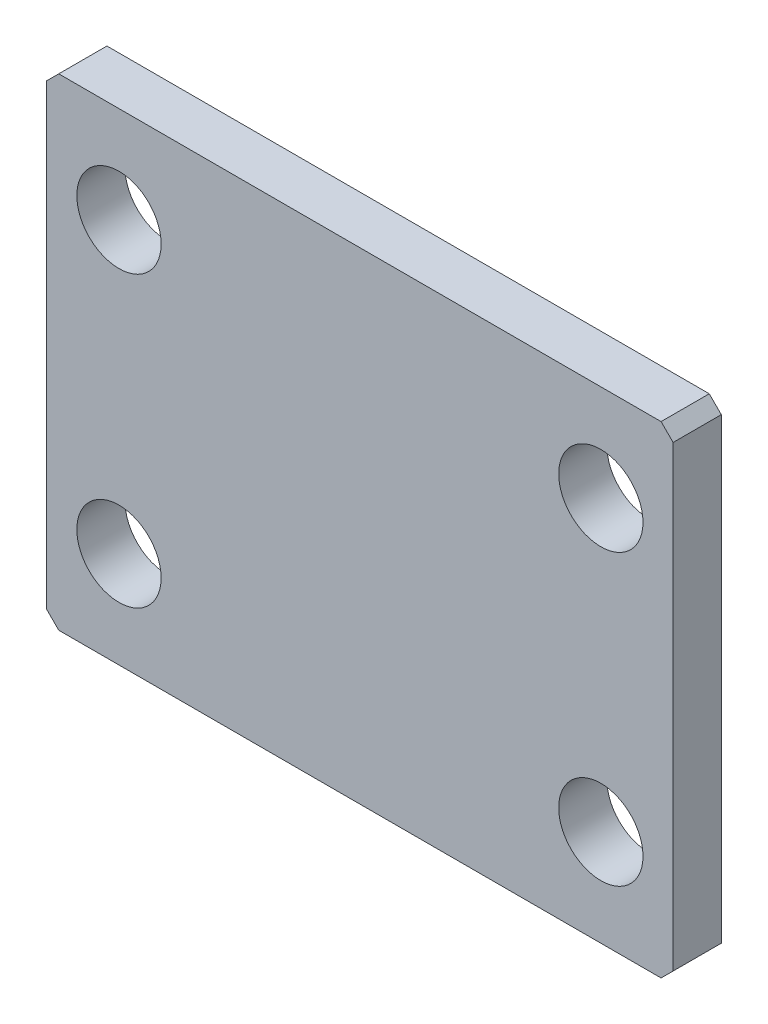
SolidWorks part; units mm, degrees
ref_plane "Front Plane" through (0, 0, 0) normal (0, 0, 1) x (1, 0, 0)
ref_plane "Top Plane" through (0, 0, 0) normal (0, 1, 0) x (1, 0, 0)
ref_plane "Right Plane" through (0, 0, 0) normal (1, 0, 0) x (0, 0, -1)
sketch "Sketch1" plane through (0, 0, 0) normal (0, 0, 1) x (1, 0, 0)
  line L0 (-25, 40) -> (25, 40) construction
  line L1 (-26, 1) -> (-26, 39) construction
  line L2 (-25, 0) -> (25, 0) construction
  line L3 (-25, 40) -> (25, 40)
  line L4 (-26, 1) -> (-26, 39)
  line L5 (-25, 0) -> (25, 0)
  line L6 (25, 40) -> (26, 39)
  line L7 (26, 1) -> (26, 39)
  line L8 (26, 1) -> (25, 0)
  line L9 (-25, 0) -> (-26, 1)
  line L10 (-26, 39) -> (-25, 40)
extrude "Boss-Extrude1" add sketch "Sketch1" along normal blind 4
sketch "Sketch2" plane through (0, 0, 4) normal (0, 0, 1) x (1, 0, 0)
  circle A0 centre (20, 32) radius 3.5
  circle A1 centre (-20, 32) radius 3.5
  circle A2 centre (20, 8) radius 3.5
  circle A3 centre (-20, 8) radius 3.5
extrude "Cut-Extrude1" cut sketch "Sketch2" against normal through all
